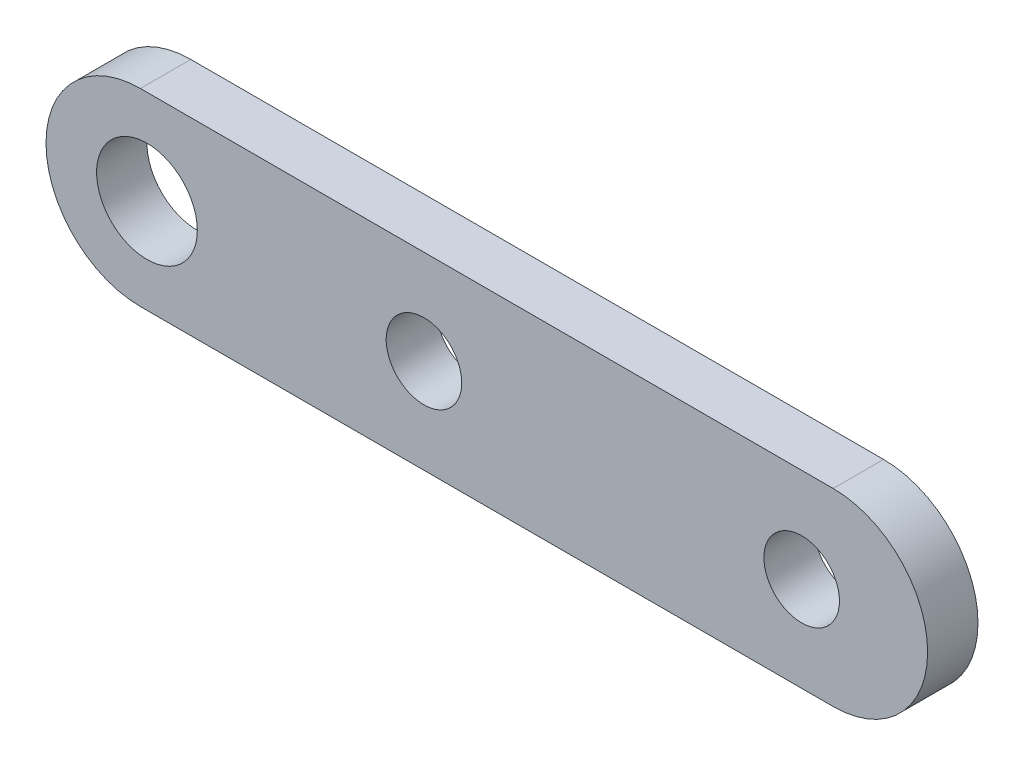
SolidWorks part; units mm, degrees
ref_plane "Спереди" through (0, 0, 0) normal (0, 0, 1) x (1, 0, 0)
ref_plane "Сверху" through (0, 0, 0) normal (0, 1, 0) x (1, 0, 0)
ref_plane "Справа" through (0, 0, 0) normal (1, 0, 0) x (0, 0, -1)
sketch "Эскиз1" plane through (0, 0, 0) normal (0, 0, 1) x (1, 0, 0)
  line L1 (7.4831, 0) -> (62.5027, 0)
  line L3 (7.4831, 15) -> (62.5027, 15)
  arc A0 (7.4831, 15) -> (7.4831, 0) centre (7.4831, 7.5) ccw
  arc A1 (62.5027, 0) -> (62.5027, 15) centre (62.5027, 7.5) ccw
extrude "Бобышка-Вытянуть1" add sketch "Эскиз1" along normal blind 4
sketch "Эскиз2" plane through (0, 0, 4) normal (0, 0, 1) x (1, 0, 0)
  circle A0 centre (8, 7.5) radius 4
  circle A1 centre (30, 7.5) radius 3
  circle A2 centre (60, 7.5) radius 3
  dimension "D1" = 8
  dimension "D3" = 6
  dimension "D6" = 6
extrude "Вырез-Вытянуть1" cut sketch "Эскиз2" against normal blind 4
